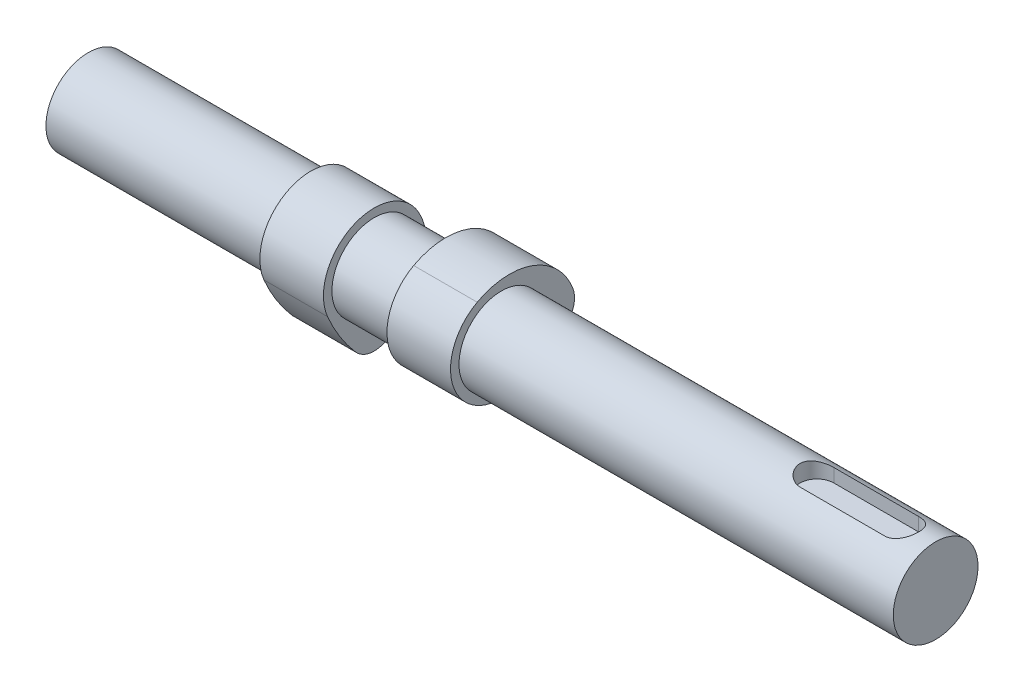
SolidWorks part; units mm, degrees
ref_plane "Front Plane" through (0, 0, 0) normal (0, 0, 1) x (1, 0, 0)
ref_plane "Top Plane" through (0, 0, 0) normal (0, 1, 0) x (1, 0, 0)
ref_plane "Right Plane" through (0, 0, 0) normal (1, 0, 0) x (0, 0, -1)
sketch "Sketch1" plane through (0, 0, 0) normal (1, 0, 0) x (0, 0, -1)
  circle A0 centre (0, 0) radius 10
  dimension "D1" = 20
extrude "Boss-Extrude1" add sketch "Sketch1" against normal blind 75 and the other way blind 125
sketch "Sketch2" plane through (0, 0, 0) normal (1, 0, 0) x (0, 0, -1)
  line L0 (0, 0) -> (11.4214, 0) construction
  arc A0 (-5.7025, 10.5585) -> (4.7241, -11.031) centre (0, 0) ccw
  arc A2 (-5.7025, 10.5585) -> (16.9082, 2.0284) centre (1.9008, -3.5195) cw
  arc A3 (4.7241, -11.031) -> (15.2659, -4.409) centre (-11.0228, 25.739) ccw
  arc A4 (15.2659, -4.409) -> (16.9082, 2.0284) centre (11.4214, 0) ccw
  dimension "D1" = 24
  dimension "D2" = 16
  dimension "D3" = 40
  dimension "D5" = 5.8498
  dimension "D4" = 12.5
extrude "Boss-Extrude2" add sketch "Sketch2" along normal mid plane 15 from offset 15 separate body
mirror "Mirror1" about plane through (0, 0, 0) normal (1, 0, 0) of bodies 102
move or copy body "Body-Move/Copy1" bodies to move or copy 103 copy no rotation origin (0, 0, 0) rotation axis (-1, 0, 0) rotation angle 90 parameters "Angle Around Edge"=90
ref_plane "Plane1" through (0, 10, 0) normal (0, 1, 0) x (1, 0, 0)
sketch "Sketch3" plane through (0, 10, 0) normal (0, 1, 0) x (1, 0, 0)
  line L0 (125, 0) -> (88.5534, 0) construction
  line L1 (125, -10) -> (125, 10) construction
  line L2 (117, 0) -> (97, 0) construction
  line L3 (117, -4) -> (97, -4)
  line L4 (117, 4) -> (97, 4)
  arc A0 (117, -4) -> (117, 4) centre (117, 0) ccw
  arc A1 (97, 4) -> (97, -4) centre (97, 0) ccw
  point P7 (107, 0)
  dimension "D3" = 4
  dimension "D1" = 20
  dimension "D2" = 8
extrude "Cut-Extrude1" cut sketch "Sketch3" against normal blind 4
